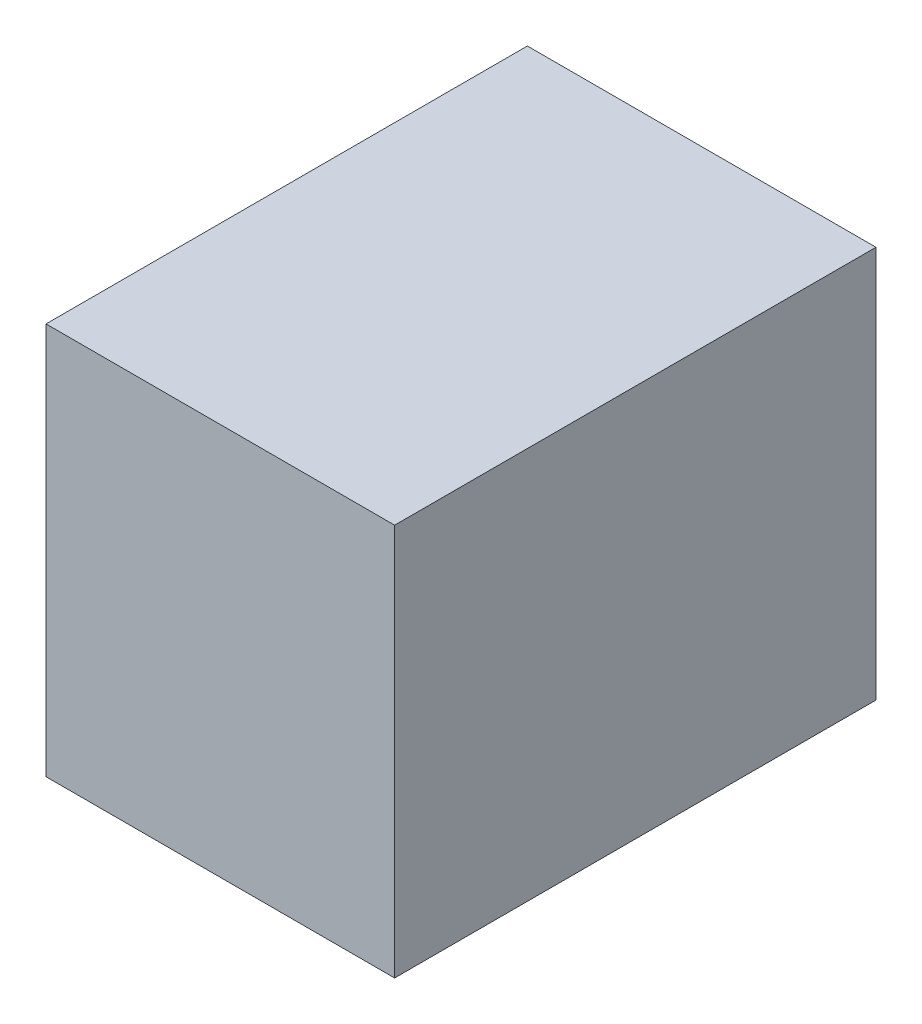
SolidWorks part; units mm, degrees
ref_plane "Front Plane" through (0, 0, 0) normal (0, 0, 1) x (1, 0, 0)
ref_plane "Top Plane" through (0, 0, 0) normal (0, 1, 0) x (1, 0, 0)
ref_plane "Right Plane" through (0, 0, 0) normal (1, 0, 0) x (0, 0, -1)
sketch "Sketch1" plane through (-82.7782, 0, 0) normal (1, 0, 0) x (0, 0, -1)
  line L1 (-594.0453, 45) -> (-538.8121, 45)
  line L2 (-594.0453, 45) -> (-594.0453, 0)
  line L3 (-594.0453, 0) -> (-538.8121, 0)
  line L4 (-538.8121, 45) -> (-538.8121, 0)
extrude "Boss-Extrude1" add sketch "Sketch1" along normal blind 40
hole_wizard "M10x1.25 Tapped Hole1" positions "Sketch2" profile "Sketch3" tap size "M10x1.25" standard "ANSI Metric"
sketch "Sketch2" plane through (-82.7782, 0, 0) normal (-1, 0, 0) x (0, 0, 1)
  point P0 (583.768, 20.3152)
  point P3 (558.768, 20.3152)
sketch "Sketch3" plane through (-82.7782, 20.3152, 583.768) normal (0, 1, 0) x (0, 0, 1)
  line L0 (0, 0) -> (0, 14.3938)
  line L1 (0, 14.3938) -> (4.4, 11.75)
  line L2 (4.4, 11.75) -> (4.4, 0)
  line L5 (4.4, 0) -> (0, 0)
  line L10 (0, 14.3938) -> (-4.4, 11.75) construction
  line L11 (0, -6.35) -> (0, 107.95) construction
  dimension "Tap Drill Dia." = 8.8
  dimension "Tap Drill Depth" = 11.75
  dimension "Drill Angle" = 118
